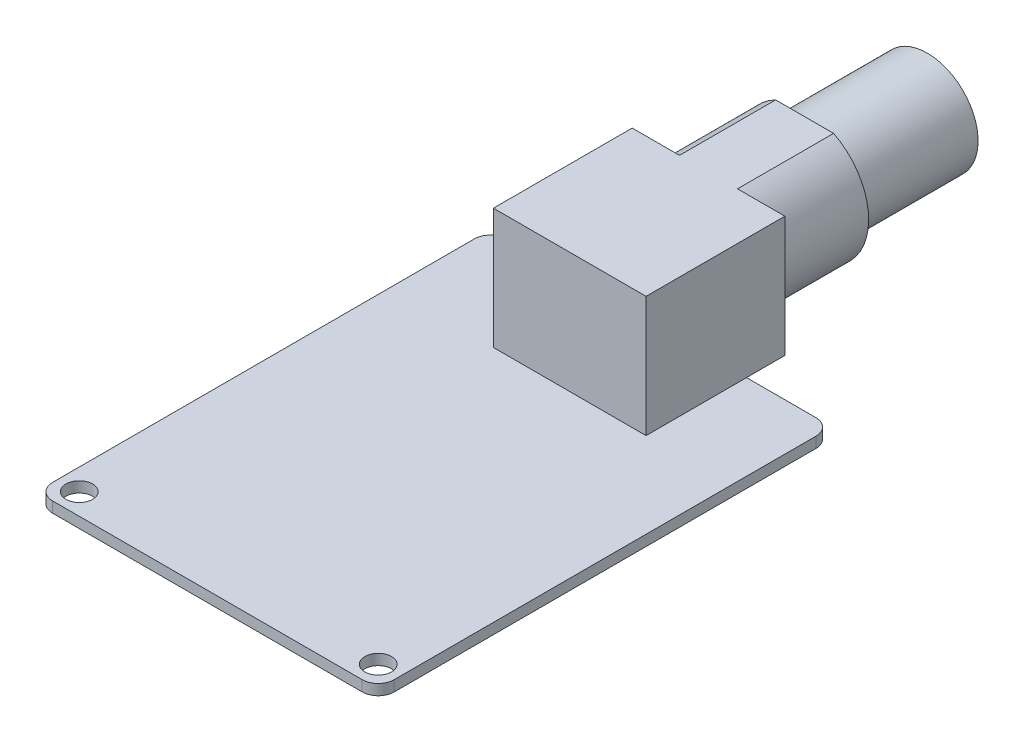
SolidWorks part; units mm, degrees
ref_plane "前基準面" through (0, 0, 0) normal (0, 0, 1) x (1, 0, 0)
ref_plane "上基準面" through (0, 0, 0) normal (0, 1, 0) x (1, 0, 0)
ref_plane "右基準面" through (0, 0, 0) normal (1, 0, 0) x (0, 0, -1)
sketch "草圖1" plane through (0, 0, 0) normal (0, 0, 1) x (1, 0, 0)
  circle A0 centre (-64.3409, 31.5) radius 6
  circle A1 centre (-64.3409, 31.5) radius 6.25 construction
  circle A2 centre (-29.3409, 31.5) radius 6.25 construction
  dimension "D1" = 12
  dimension "D2" = 0
  dimension "D3" = 35
extrude "填料-伸長1" add sketch "草圖1" against normal blind 5.5 and the other way blind 3.5 contours A0
sketch "草圖2" plane through (0, 0, 3.5) normal (0, 0, 1) x (1, 0, 0)
  line L1 (-71.4909, 36.85) -> (-57.1909, 36.85)
  line L2 (-71.4909, 36.85) -> (-71.4909, 25.55)
  line L3 (-71.4909, 25.55) -> (-57.1909, 25.55)
  line L4 (-57.1909, 36.85) -> (-57.1909, 25.55)
  circle A0 centre (-64.3409, 31.5) radius 6 construction
  dimension "D5" = 5.95
  dimension "D1" = 7.15
  dimension "D3" = 11.3
  dimension "D4" = 14.3
extrude "填料-伸長2" add sketch "草圖2" along normal blind 13
sketch "草圖3" plane through (0, 25.55, 0) normal (0, -1, 0) x (1, 0, 0)
  line L0 (-57.1909, 16.5) -> (-57.1909, 3.5) construction
  line L1 (-50.6909, 7.0879) -> (-79.6909, 7.0879)
  line L2 (-49.1909, 8.5879) -> (-49.1909, 48.0879)
  line L3 (-50.6909, 49.5879) -> (-79.6909, 49.5879)
  line L4 (-81.1909, 8.5879) -> (-81.1909, 48.0879)
  circle A0 centre (-51.1909, 47.5879) radius 1.25
  circle A1 centre (-79.1909, 47.5879) radius 1.25
  arc A2 (-79.6909, 7.0879) -> (-81.1909, 8.5879) centre (-79.6909, 8.5879) cw
  arc A3 (-50.6909, 7.0879) -> (-49.1909, 8.5879) centre (-50.6909, 8.5879) ccw
  arc A4 (-79.6909, 49.5879) -> (-81.1909, 48.0879) centre (-79.6909, 48.0879) ccw
  arc A5 (-49.1909, 48.0879) -> (-50.6909, 49.5879) centre (-50.6909, 48.0879) ccw
  point P14 (-81.1909, 7.0879)
  point P19 (-81.1909, 49.5879)
  point P22 (-49.1909, 49.5879)
  dimension "D4" = 2.5
  dimension "D5" = 2.5
  dimension "D6" = 2
  dimension "D10" = 1.5
  dimension "D1" = 32
  dimension "D2" = 42.5
  dimension "D3" = 8
  dimension "D7" = 2
  dimension "D8" = 2
  dimension "D9" = 2
extrude "填料-伸長3" add sketch "草圖3" along normal blind 1
sketch "草圖4" plane through (0, 0, -5.5) normal (0, 0, -1) x (-1, 0, 0)
  circle A0 centre (64.3409, 31.5) radius 4.75
  circle A1 centre (64.3409, 31.5) radius 6 construction
  dimension "D1" = 9.5
  dimension "D2" = 0
extrude "填料-伸長4" add sketch "草圖4" along normal blind 11.5
sketch "草圖5" plane through (0, 0, -17) normal (0, 0, -1) x (-1, 0, 0)
  circle A3 centre (64.3409, 31.5) radius 4.25
  circle A4 centre (64.3409, 31.5) radius 4.25
  dimension "D1" = 0.5
extrude "除料-伸長1" cut sketch "草圖5" against normal blind 11.5
sketch "草圖6" plane through (0, 0, 3.5) normal (0, 0, 1) x (1, 0, 0)
  line L1 (-67.0571, 36.85) -> (-61.6248, 36.85)
  line L2 (-67.0571, 36.85) -> (-61.6248, 36.85)
  arc A1 (-61.6248, 36.85) -> (-67.0571, 36.85) centre (-64.3409, 31.5) ccw
  arc A2 (-61.6248, 36.85) -> (-67.0571, 36.85) centre (-64.3409, 31.5) ccw
  dimension "D1" = 0
extrude "除料-伸長2" cut sketch "草圖6" against normal up to next
